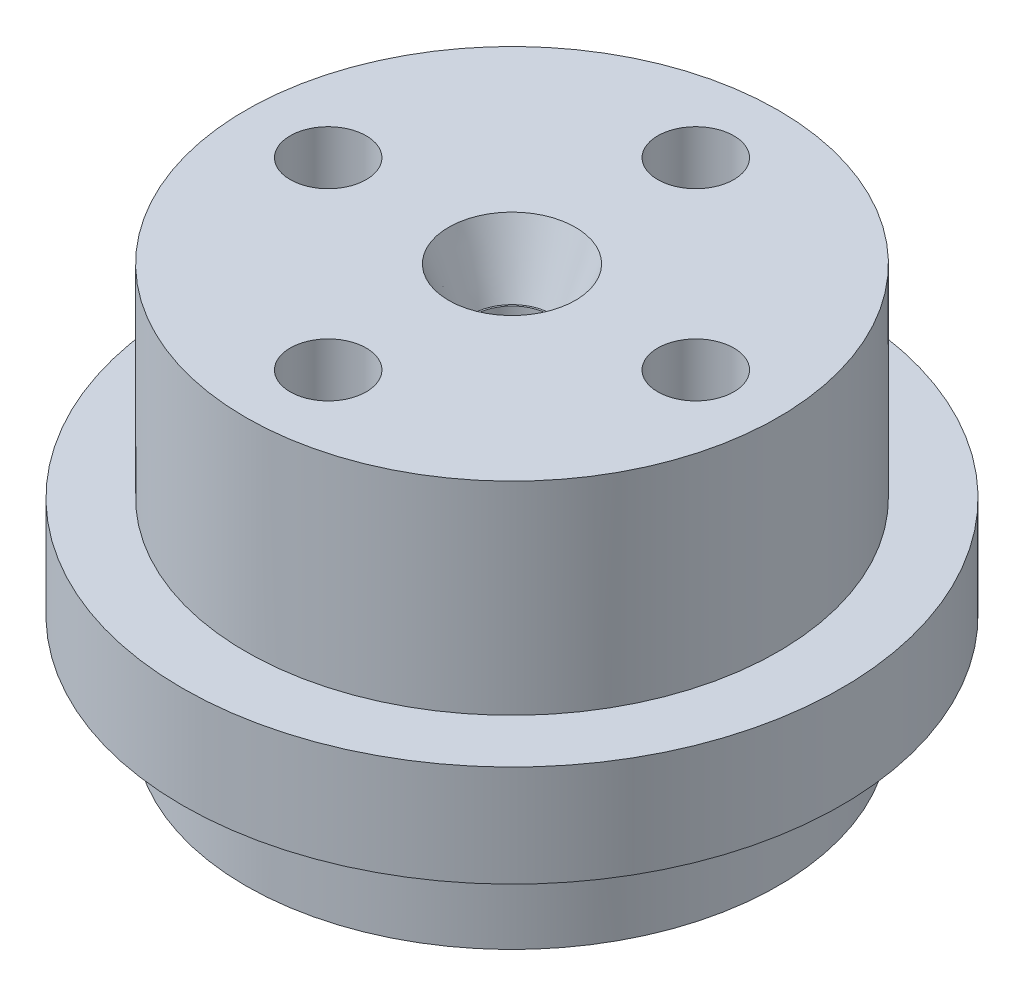
SolidWorks part; units mm, degrees
ref_plane "Front Plane" through (0, 0, 0) normal (0, 0, 1) x (1, 0, 0)
ref_plane "Top Plane" through (0, 0, 0) normal (0, 1, 0) x (1, 0, 0)
ref_plane "Right Plane" through (0, 0, 0) normal (1, 0, 0) x (0, 0, -1)
sketch "Sketch1" plane through (0, 0, 0) normal (0, 1, 0) x (1, 0, 0)
  circle A0 centre (0, 0) radius 10.5
extrude "Boss-Extrude1" add sketch "Sketch1" along normal blind 16
sketch "Sketch2" plane through (0, 16, 0) normal (0, 1, 0) x (1, 0, 0)
  circle A0 centre (0, 0) radius 1.5
extrude "Cut-Extrude1" cut sketch "Sketch2" against normal through all
sketch "Sketch3" plane through (0, 16, 0) normal (0, 1, 0) x (1, 0, 0)
  circle A0 centre (0, 0) radius 2.5
extrude "Cut-Extrude2" cut sketch "Sketch3" against normal blind 2.5 draft 20.5
ref_plane "Plane1" through (0, 6, 0) normal (0, -1, 0) x (-1, 0, 0)
sketch "Sketch5" plane through (0, 6, 0) normal (0, -1, 0) x (-1, 0, 0)
  circle A0 centre (0, 0) radius 13
extrude "Boss-Extrude2" add sketch "Sketch5" along normal blind 2 and the other way blind 2
sketch "Sketch7" plane through (0, 16, 0) normal (0, 1, 0) x (1, 0, 0)
  circle A0 centre (0, 7.25) radius 1.5
  circle A1 centre (7.25, 0) radius 1.5
  circle A2 centre (0, -7.25) radius 1.5
  circle A3 centre (-7.25, 0) radius 1.5
  point P12 (0, 0)
  dimension "D2" = 4
extrude "Cut-Extrude3" cut sketch "Sketch7" against normal blind 10
cosmetic thread "Cosmetic Thread1" parameters "D2"=4
cosmetic thread "Cosmetic Thread2" parameters "D2"=4
cosmetic thread "Cosmetic Thread3" parameters "D2"=4
cosmetic thread "Cosmetic Thread4" parameters "D2"=4
sketch "Sketch8" plane through (0, 6, 0) normal (0, 1, 0) x (1, 0, 0)
  circle A0 centre (-7.25, 0) radius 1
  circle A1 centre (0, 7.25) radius 1
  circle A2 centre (7.25, 0) radius 1
  circle A3 centre (0, -7.25) radius 1
  point P12 (0, 0)
  dimension "D1" = 4
extrude "Cut-Extrude4" cut sketch "Sketch8" against normal through all
cosmetic thread "Cosmetic Thread5" parameters "D2"=2.5
cosmetic thread "Cosmetic Thread6" parameters "D2"=2.5
cosmetic thread "Cosmetic Thread7" parameters "D2"=2.5
cosmetic thread "Cosmetic Thread8" parameters "D2"=2.5
sketch "Sketch9" plane through (0, 16, 0) normal (0, 1, 0) x (1, 0, 0)
  circle A0 centre (0, 0) radius 1.5
extrude "Cut-Extrude5" cut sketch "Sketch9" against normal through all
